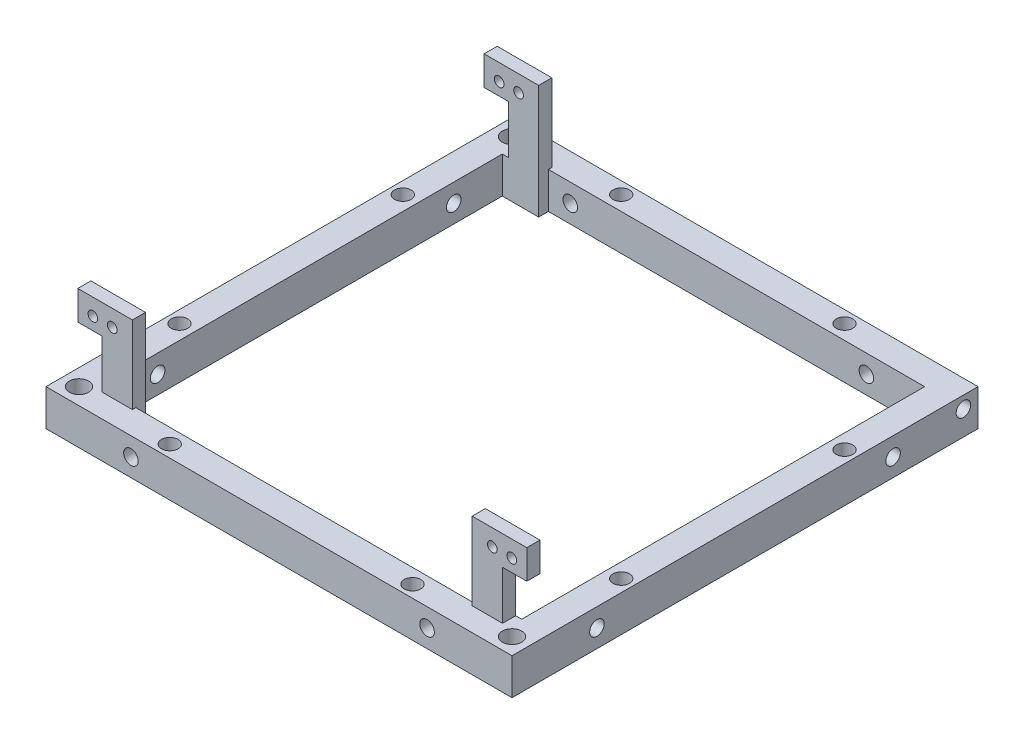
SolidWorks part; units mm, degrees
material "Aluminum"
ref_plane "Front Plane" through (0, 0, 0) normal (0, 0, 1) x (1, 0, 0)
ref_plane "Top Plane" through (0, 0, 0) normal (0, 1, 0) x (1, 0, 0)
ref_plane "Right Plane" through (0, 0, 0) normal (1, 0, 0) x (0, 0, -1)
sketch "Sketch1" plane through (0, 0, 0) normal (0, 1, 0) x (1, 0, 0)
  line L1 (48, -48) -> (-48, -48)
  line L2 (48, -48) -> (48, 48)
  line L3 (48, 48) -> (-48, 48)
  line L4 (-48, -48) -> (-48, 48)
  line L5 (48, -48) -> (-48, 48) construction
  line L6 (48, 48) -> (-48, -48) construction
  line L7 (40, -40) -> (-40, -40)
  line L8 (40, -40) -> (40, 40)
  line L9 (40, 40) -> (-40, 40)
  line L10 (-40, -40) -> (-40, 40)
  line L11 (40, -40) -> (-40, 40) construction
  line L12 (40, 40) -> (-40, -40) construction
  point P0 (0, 0)
  point P6 (0, 0)
  dimension "D1" = 96
  dimension "D2" = 96
  dimension "D3" = 8
extrude "Boss-Extrude1" add sketch "Sketch1" along normal blind 8
sketch "Sketch27" plane through (0, 8, 0) normal (0, 1, 0) x (1, 0, 0)
  line L0 (-40, 40) -> (-40, -40) construction
  line L1 (41, -41) -> (-41, -41)
  line L2 (41, -41) -> (41, 41)
  line L3 (41, 41) -> (-41, 41)
  line L4 (-41, -41) -> (-41, 41)
  line L5 (41, -41) -> (-41, 41) construction
  line L6 (41, 41) -> (-41, -41) construction
  line L7 (40, 40) -> (-40, 40) construction
  point P0 (0, 0)
  dimension "D1" = 1
  dimension "D2" = 1
extrude "Cut-Extrude2" cut sketch "Sketch27" against normal blind 10
hole_wizard "Ø3.0 (3) Diameter Hole1" positions "Sketch30" profile "Sketch29" hole size "Ø3.0" standard "ANSI Metric" end condition through all
sketch "Sketch30" plane through (0, 0, 48) normal (0, 0, 1) x (1, 0, 0)
  point P0 (-30.5, 2.7)
  point P4 (30.5, 2.7)
sketch "Sketch29" plane through (-30.5, 2.7, 48) normal (1, 0, 0) x (0, -1, 0)
  line L0 (0, 0) -> (0, 96)
  line L1 (0, 96) -> (1.5, 96)
  line L2 (1.5, 96) -> (1.5, 0)
  line L5 (1.5, 0) -> (0, 0)
  line L11 (0, -6.35) -> (0, 107.95) construction
  dimension "Thru Hole Dia." = 3
  dimension "Thru Hole Depth" = 96
hole_wizard "Ø3.4 (3.4) Diameter Hole1" positions "Sketch37" profile "Sketch36" hole size "Ø3.4" standard "ANSI Metric" end condition through all
sketch "Sketch37" plane through (0, 0, 0) normal (0, -1, 0) x (-1, 0, 0)
  point P0 (-23, 45.5)
  point P2 (23, 45.5)
  point P4 (45.5, 23)
  point P6 (45.5, -23)
  point P8 (25, -45.5)
  point P10 (-25, -45.5)
  point P12 (-45.5, -23)
  point P14 (-45.5, 23)
sketch "Sketch36" plane through (23, 0, -45.5) normal (1, 0, 0) x (0, 0, -1)
  line L0 (0, 0) -> (0, 8)
  line L1 (0, 8) -> (1.7, 8)
  line L2 (1.7, 8) -> (1.7, 0)
  line L5 (1.7, 0) -> (0, 0)
  line L11 (0, -6.35) -> (0, 107.95) construction
  dimension "Thru Hole Dia." = 3.4
  dimension "Thru Hole Depth" = 8
sketch "Sketch38" plane through (0, 8, 0) normal (0, 1, 0) x (1, 0, 0)
  line L0 (48, 48) -> (-48, 48) construction
  line L1 (42.5, -42.5) -> (-42.5, -42.5)
  line L2 (42.5, -42.5) -> (42.5, 42.5)
  line L3 (42.5, 42.5) -> (-42.5, 42.5)
  line L4 (-42.5, -42.5) -> (-42.5, 42.5)
  line L5 (42.5, -42.5) -> (-42.5, 42.5) construction
  line L6 (42.5, 42.5) -> (-42.5, -42.5) construction
  line L7 (-48, 48) -> (-48, -48) construction
  point P0 (0, 0)
  dimension "D1" = 5.5
  dimension "D2" = 5.5
extrude "Cut-Extrude4" cut sketch "Sketch38" against normal blind 10
hole_wizard "Ø3.0 (3) Diameter Hole7" positions "Sketch40" profile "Sketch41" hole size "Ø3.0" standard "ISO" end condition through all
sketch "Sketch40" plane through (-48, 0, 0) normal (-1, 0, 0) x (0, 0, 1)
  line L0 (0, 0) -> (0, 8) construction
  line L1 (-48, 0) -> (48, 0) construction
  line L2 (-48, 8) -> (48, 8) construction
  point P0 (-30.5, 2.7)
  point P2 (30.5, 2.7)
  dimension "D1" = 61
  dimension "D2" = 30.5
sketch "Sketch41" plane through (-48, 2.7, -30.5) normal (0, 1, 0) x (0, 0, 1)
  line L0 (0, 0) -> (0, 96)
  line L1 (0, 96) -> (1.5, 96)
  line L2 (1.5, 96) -> (1.5, 0)
  line L5 (1.5, 0) -> (0, 0)
  line L11 (0, -6.35) -> (0, 107.95) construction
  dimension "Thru Hole Dia." = 3
  dimension "Thru Hole Depth" = 96
sketch "Sketch44" plane through (0, 0, 0) normal (0, -1, 0) x (1, 0, 0)
  line L0 (42.5, -42.5) -> (-42.5, -42.5) construction
  line L1 (42.5, -42.5) -> (38.5, -42.5)
  line L2 (42.5, -42.5) -> (42.5, -38.5)
  line L3 (42.5, -38.5) -> (38.5, -38.5)
  line L4 (38.5, -42.5) -> (38.5, -38.5)
  line L5 (42.5, 42.5) -> (42.5, -42.5) construction
  line L6 (0, 0) -> (0, -67.1068) construction
  line L7 (0, 0) -> (66.4168, 0) construction
  line L8 (-38.5, -42.5) -> (-38.5, -38.5)
  line L9 (-42.5, -38.5) -> (-38.5, -38.5)
  line L10 (-42.5, -42.5) -> (-42.5, -38.5)
  line L11 (-42.5, -42.5) -> (-38.5, -42.5)
  line L12 (-42.5, 42.5) -> (-38.5, 42.5)
  line L13 (-42.5, 42.5) -> (-42.5, 38.5)
  line L14 (-42.5, 38.5) -> (-38.5, 38.5)
  line L15 (-38.5, 42.5) -> (-38.5, 38.5)
  line L16 (38.5, 42.5) -> (38.5, 38.5)
  line L17 (42.5, 38.5) -> (38.5, 38.5)
  line L18 (42.5, 42.5) -> (42.5, 38.5)
  line L19 (42.5, 42.5) -> (38.5, 42.5)
  dimension "D1" = 4
  dimension "D2" = 4
extrude "Boss-Extrude2" add sketch "Sketch44" against normal blind 8
sketch "Sketch45" plane through (0, 8, 0) normal (0, 1, 0) x (1, 0, 0)
  line L1 (-42.5, 38.5) -> (-38.5, 38.5)
  line L2 (-42.5, 38.5) -> (-42.5, 35)
  line L3 (-42.5, 35) -> (-38.5, 35)
  line L4 (-38.5, 38.5) -> (-38.5, 35)
  dimension "D1" = 4
  dimension "D2" = 3.5
extrude "Boss-Extrude3" add sketch "Sketch45" against normal blind 8
sketch "Sketch49" plane through (48, 0, 0) normal (1, 0, 0) x (0, 0, -1)
  line L0 (48, 8) -> (48, 0) construction
  line L1 (-48, 8) -> (48, 8)
  line L2 (-48, 8) -> (-48, 6.5)
  line L3 (-48, 6.5) -> (48, 6.5)
  line L4 (48, 8) -> (48, 6.5)
  dimension "D1" = 1.5
extrude "Cut-Extrude5" cut sketch "Sketch49" against normal blind 146
hole_wizard "Tap Drill for M4 Tap1" positions "Sketch51" profile "Sketch50" hole size "M4" standard "ISO" end condition through all
sketch "Sketch51" plane through (0, 6.5, 0) normal (0, 1, 0) x (1, 0, 0)
  line L1 (-48, -48) -> (48, -48) construction
  line L2 (48, -48) -> (48, 48) construction
  line L3 (-48, -48) -> (-48, 48) construction
  line L4 (-48, 48) -> (48, 48) construction
  point P0 (44.6, -44.6)
  point P4 (-44.6, -44.6)
  point P6 (-44.6, 44.6)
  dimension "D1" = 3.4
  dimension "D2" = 3.4
  dimension "D3" = 3.4
  dimension "D4" = 3.4
  dimension "D5" = 3.4
  dimension "D6" = 3.4
sketch "Sketch50" plane through (44.6, 6.5, 44.6) normal (1, 0, 0) x (0, 0, 1)
  line L0 (0, 0) -> (0, 6.5)
  line L1 (0, 6.5) -> (2, 6.5)
  line L2 (2, 6.5) -> (2, 0)
  line L5 (2, 0) -> (0, 0)
  line L11 (0, -6.35) -> (0, 107.95) construction
  dimension "Thru Hole Dia." = 4
  dimension "Thru Hole Depth" = 6.5
sketch "Sketch53" plane through (-38.5, 0, 0) normal (1, 0, 0) x (0, 0, -1)
  line L1 (-42.5, 6.5) -> (-38.5, 6.5)
  line L2 (-42.5, 6.5) -> (-42.5, 0)
  line L3 (-42.5, 0) -> (-38.5, 0)
  line L4 (-38.5, 6.5) -> (-38.5, 0)
extrude "Boss-Extrude5" add sketch "Sketch53" along normal blind 78
sketch "Sketch54" plane through (0, 6.5, 0) normal (0, 1, 0) x (1, 0, 0)
  line L0 (42.5, -38.5) -> (-42.5, -38.5) construction
  line L1 (-42.5, 35) -> (-42.5, -38.5) construction
  line L2 (-48, -48) -> (48, -48) construction
  line L3 (-41.25, -40.5) -> (-41.25, -43.2)
  line L6 (0, -38.5) -> (0, -84.4574) construction
  line L7 (-35, -40.5) -> (-35, -43.2)
  line L8 (-41.25, -43.2) -> (-35, -43.2)
  line L10 (-41.25, -40.5) -> (-35, -40.5)
  line L11 (0, 0) -> (25.8217, 0) construction
  dimension "D1" = 2.7
  dimension "D2" = 4.8
  dimension "D3" = 6.25
  dimension "D4" = 1.25
  dimension "D5" = 6.25
  dimension "D6" = 2.7
sketch "Sketch57" plane through (0, 0, -35) normal (0, 0, 1) x (1, 0, 0)
  line L1 (-42.5, 6.5) -> (-38.5, 6.5)
  line L2 (-42.5, 6.5) -> (-42.5, 0)
  line L3 (-42.5, 0) -> (-38.5, 0)
  line L4 (-38.5, 6.5) -> (-38.5, 0)
extrude "Cut-Extrude6" cut sketch "Sketch57" against normal blind 7.5
sketch "Sketch58" plane through (38.5, 0, 0) normal (-1, 0, 0) x (0, 0, 1)
  line L1 (-42.5, 6.5) -> (-38.5, 6.5)
  line L2 (-42.5, 6.5) -> (-42.5, 0)
  line L3 (-42.5, 0) -> (-38.5, 0)
  line L4 (-38.5, 6.5) -> (-38.5, 0)
extrude "Boss-Extrude7" add sketch "Sketch58" along normal blind 81
sketch "Sketch61" plane through (0, 6.5, 0) normal (0, 1, 0) x (1, 0, 0)
  line L0 (-48, 48) -> (48, 48) construction
  line L1 (-16, 42.5) -> (16, 42.5)
  line L2 (-16, 42.5) -> (-16, -42.5)
  line L3 (-16, -42.5) -> (16, -42.5)
  line L4 (16, 42.5) -> (16, -42.5)
  line L5 (-48, -48) -> (48, -48) construction
  dimension "D1" = 5.5
  dimension "D2" = 5.5
  dimension "D3" = 16
  dimension "D4" = 16
extrude "Cut-Extrude7" cut sketch "Sketch61" against normal blind 81
sketch "Sketch66" plane through (0, 6.5, 0) normal (0, 1, 0) x (1, 0, 0)
  line L0 (42.5, -38.5) -> (42.5, 38.5) construction
  line L1 (42.5, 40.099) -> (-42.5, 40.099)
  line L2 (42.5, 40.099) -> (42.5, -40.099)
  line L3 (42.5, -40.099) -> (-42.5, -40.099)
  line L4 (-42.5, 40.099) -> (-42.5, -40.099)
  line L5 (-42.5, 38.5) -> (-42.5, -38.5) construction
extrude "Cut-Extrude8" cut sketch "Sketch66" against normal blind 10
sketch "Sketch67" plane through (0, 0, 0) normal (0, -1, 0) x (1, 0, 0)
  line L0 (42.5, 40.099) -> (42.5, -40.099) construction
  line L1 (-42.5, 42.5) -> (42.5, 42.5)
  line L2 (-42.5, 42.5) -> (-42.5, -42.5)
  line L3 (-42.5, -42.5) -> (42.5, -42.5)
  line L4 (42.5, 42.5) -> (42.5, -42.5)
  line L5 (-16, 42.5) -> (16, 42.5) construction
  line L6 (-42.5, -40.099) -> (-42.5, 40.099) construction
  line L7 (16, -42.5) -> (-16, -42.5) construction
extrude "Cut-Extrude9" cut sketch "Sketch67" against normal blind 3.5
sketch "Sketch68" plane through (0, 6.5, 0) normal (0, 1, 0) x (1, 0, 0)
  line L1 (26, 42.5) -> (-26, 42.5)
  line L2 (26, 42.5) -> (26, -42.5)
  line L3 (26, -42.5) -> (-26, -42.5)
  line L4 (-26, 42.5) -> (-26, -42.5)
  line L5 (0, 0) -> (0, 30.6776) construction
  line L6 (16, 42.5) -> (-16, 42.5) construction
  dimension "D1" = 26
  dimension "D2" = 26
extrude "Cut-Extrude10" cut sketch "Sketch68" against normal blind 56
extrude "Boss-Extrude8" add sketch "Sketch54" along normal blind 16
mirror "Mirror1" about plane through (0, 0, 0) normal (1, 0, 0) of "Boss-Extrude8"
sketch "Sketch75" plane through (26, 0, 0) normal (-1, 0, 0) x (0, 0, 1)
  line L1 (40.099, 6.5) -> (42.5, 6.5)
  line L2 (40.099, 6.5) -> (40.099, 3.5)
  line L3 (40.099, 3.5) -> (42.5, 3.5)
  line L4 (42.5, 6.5) -> (42.5, 3.5)
extrude "Cut-Extrude12" cut sketch "Sketch75" against normal blind 10.22 and the other way blind 62.22
mirror "Mirror2" about plane through (0, 0, 0) normal (0, 0, 1) of "Boss-Extrude8"
mirror "Mirror3" about plane through (0, 0, 0) normal (0, 0, 1) of "Cut-Extrude12"
sketch "Sketch77" plane through (36.22, 0, 0) normal (-1, 0, 0) x (0, 0, 1)
  line L1 (-42.5, 6.5) -> (-40.099, 6.5)
  line L2 (-42.5, 6.5) -> (-42.5, 3.5)
  line L3 (-42.5, 3.5) -> (-40.099, 3.5)
  line L4 (-40.099, 6.5) -> (-40.099, 3.5)
extrude "Cut-Extrude13" cut sketch "Sketch77" against normal blind 6.28
sketch "Sketch78" plane through (0, 0, 0) normal (0, -1, 0) x (1, 0, 0)
  line L1 (-42.5, 42.5) -> (42.5, 42.5)
  line L2 (-42.5, 42.5) -> (-42.5, -42.5)
  line L3 (-42.5, -42.5) -> (42.5, -42.5)
  line L4 (42.5, 42.5) -> (42.5, -42.5)
extrude "Cut-Extrude14" cut sketch "Sketch78" against normal blind 6.5
sketch "Sketch79" plane through (0, 0, 0) normal (0, -1, 0) x (1, 0, 0)
  line L0 (40.5, -40.5) -> (40.5, 40.5)
  line L1 (42.5, -42.5) -> (-42.5, -42.5)
  line L2 (42.5, -42.5) -> (42.5, 42.5)
  line L3 (42.5, 42.5) -> (-42.5, 42.5)
  line L4 (-42.5, -42.5) -> (-42.5, 42.5)
  line L5 (40.5, 40.5) -> (-40.5, 40.5)
  line L6 (-40.5, -40.5) -> (-40.5, 40.5)
  line L7 (40.5, -40.5) -> (-40.5, -40.5)
  dimension "D1" = 2
extrude "Boss-Extrude12" add sketch "Sketch79" against normal blind 6.5
sketch "Sketch81" plane through (-41.25, 0, 0) normal (-1, 0, 0) x (0, 0, 1)
  line L0 (43.2, 22.5) -> (43.2, 6.5) construction
  line L1 (40.5, 22.5) -> (43.2, 22.5)
  line L2 (40.5, 22.5) -> (40.5, 16.5)
  line L3 (40.5, 16.5) -> (43.2, 16.5)
  line L4 (43.2, 22.5) -> (43.2, 16.5)
  dimension "D1" = 6
extrude "Boss-Extrude13" add sketch "Sketch81" along normal blind 5
mirror "Mirror4" about plane through (0, 0, 0) normal (0, 0, 1) of "Boss-Extrude13"
mirror "Mirror5" about plane through (0, 0, 0) normal (1, 0, 0) of "Boss-Extrude13"
hole_wizard "Tap Drill for M2 Tap1" positions "Sketch83" profile "Sketch82" hole size "M2" standard "ISO"
sketch "Sketch83" plane through (0, 0, 40.5) normal (0, 0, -1) x (-1, 0, 0)
  point P0 (39.1473, 19.1)
  point P3 (43.1473, 19.1)
  point P6 (-39.15, 19.1)
  point P9 (-43.15, 19.1)
sketch "Sketch82" plane through (-39.1473, 19.1, 40.5) normal (1, 0, 0) x (0, 1, 0)
  line L0 (0, 0) -> (0, 5.5)
  line L1 (0, 5.5) -> (1, 5.5)
  line L2 (1, 5.5) -> (1, 0)
  line L5 (1, 0) -> (0, 0)
  line L10 (0, 5.5) -> (-1, 5.5) construction
  line L11 (0, -6.35) -> (0, 107.95) construction
  dimension "Hole Dia." = 2
  dimension "Hole Depth" = 5.5
  dimension "Drill Angle" = 180
hole_wizard "Tap Drill for M2 Tap2" positions "Sketch85" profile "Sketch84" hole size "M2" standard "ISO"
sketch "Sketch85" plane through (0, 0, -40.5) normal (0, 0, 1) x (1, 0, 0)
  point P0 (-39.1473, 19.1)
  point P3 (-43.1473, 19.1)
sketch "Sketch84" plane through (-39.1473, 19.1, -40.5) normal (1, 0, 0) x (0, -1, 0)
  line L0 (0, 0) -> (0, 5.5)
  line L1 (0, 5.5) -> (1, 5.5)
  line L2 (1, 5.5) -> (1, 0)
  line L5 (1, 0) -> (0, 0)
  line L10 (0, 5.5) -> (-1, 5.5) construction
  line L11 (0, -6.35) -> (0, 107.95) construction
  dimension "Hole Dia." = 2
  dimension "Hole Depth" = 5.5
  dimension "Drill Angle" = 180
hole_wizard "Tap Drill for M3x0.5 Tap1" positions "Sketch87" profile "Sketch86" hole size "M3x0.5" standard "ANSI Metric"
sketch "Sketch87" plane through (48, 0, 0) normal (1, 0, 0) x (0, 0, -1)
  point P0 (45, 4)
sketch "Sketch86" plane through (48, 4, -45) normal (0, 1, 0) x (0, 0, -1)
  line L0 (0, 0) -> (0, 7.5)
  line L1 (0, 7.5) -> (1.5, 7.5)
  line L2 (1.5, 7.5) -> (1.5, 0)
  line L5 (1.5, 0) -> (0, 0)
  line L10 (0, 7.5) -> (-1.5, 7.5) construction
  line L11 (0, -6.35) -> (0, 107.95) construction
  dimension "Hole Dia." = 3
  dimension "Hole Depth" = 7.5
  dimension "Drill Angle" = 180
sketch "Sketch88" plane through (0, 6.5, 0) normal (0, 1, 0) x (1, 0, 0)
  line L0 (40.5, 40.5) -> (40.5, -40.5) construction
  line L1 (40.5, 35) -> (42.5, 35)
  line L2 (40.5, 35) -> (40.5, -35)
  line L3 (40.5, -35) -> (42.5, -35)
  line L4 (42.5, 35) -> (42.5, -35)
  line L5 (-35, 40.5) -> (40.5, 40.5) construction
  line L6 (35, -40.5) -> (-35, -40.5) construction
  line L7 (-40.5, -40.5) -> (-40.5, 40.5) construction
  line L8 (35, -40.5) -> (-35, -40.5)
  line L9 (35, -40.5) -> (35, -42.5)
  line L10 (35, -42.5) -> (-35, -42.5)
  line L11 (-35, -40.5) -> (-35, -42.5)
  line L13 (-40.5, -35) -> (-42.5, -35)
  line L14 (-40.5, -35) -> (-40.5, 35)
  line L15 (-40.5, 35) -> (-42.5, 35)
  line L16 (-42.5, -35) -> (-42.5, 35)
  line L17 (35, 40.5) -> (-35, 40.5)
  line L18 (35, 40.5) -> (35, 42.5)
  line L19 (35, 42.5) -> (-35, 42.5)
  line L20 (-35, 40.5) -> (-35, 42.5)
  dimension "D1" = 5.5
  dimension "D2" = 5.5
  dimension "D3" = 2
  dimension "D4" = 2
  dimension "D5" = 5.5
  dimension "D6" = 5.5
  dimension "D7" = 5.5
  dimension "D8" = 5.5
  dimension "D9" = 2
  dimension "D10" = 2
  dimension "D11" = 5.5
  dimension "D12" = 5.5
extrude "Cut-Extrude15" cut sketch "Sketch88" against normal blind 10
sketch "Sketch89" plane through (0, 6.5, 0) normal (0, 1, 0) x (1, 0, 0)
  line L0 (-35, 40.5) -> (-46.25, 40.5) construction
  line L1 (-42.5, 40.5) -> (42.5, 40.5)
  line L2 (-42.5, 40.5) -> (-42.5, -40.5)
  line L3 (-42.5, -40.5) -> (42.5, -40.5)
  line L4 (42.5, 40.5) -> (42.5, -40.5)
  line L5 (35, -40.5) -> (46.25, -40.5) construction
extrude "Cut-Extrude16" cut sketch "Sketch89" against normal blind 10
sketch "Sketch90" plane through (35, 0, 0) normal (-1, 0, 0) x (0, 0, 1)
  line L1 (-42.5, 0) -> (-40.5, 0)
  line L2 (-42.5, 0) -> (-42.5, 6.5)
  line L3 (-42.5, 6.5) -> (-40.5, 6.5)
  line L4 (-40.5, 0) -> (-40.5, 6.5)
extrude "Cut-Extrude17" cut sketch "Sketch90" against normal blind 7.5
sketch "Sketch91" plane through (0, 0, 0) normal (0, -1, 0) x (1, 0, 0)
  line L1 (-48, 48) -> (48, 48)
  line L2 (-48, 48) -> (-48, -48)
  line L3 (-48, -48) -> (48, -48)
  line L4 (48, 48) -> (48, -48)
  line L5 (42.5, -42.5) -> (-35, -42.5)
  line L6 (42.5, -42.5) -> (42.5, 40.5)
  line L7 (35, 42.5) -> (-35, 42.5)
  line L8 (-42.5, -40.5) -> (-42.5, 40.5)
  line L9 (-35, 40.5) -> (-42.5, 40.5)
  line L10 (-35, 40.5) -> (-35, 42.5)
  line L13 (35, 40.5) -> (42.5, 40.5)
  line L14 (35, 40.5) -> (35, 42.5)
  line L19 (-42.5, -40.5) -> (-35, -40.5)
  line L20 (-35, -42.5) -> (-35, -40.5)
  circle A0 centre (-25, 45.5) radius 1.7
  circle A1 centre (25, 45.5) radius 1.6454
  circle A2 centre (44.6, 44.6) radius 2
  circle A3 centre (45.5, 23) radius 1.7
  circle A4 centre (45.5, -23) radius 1.7
  circle A5 centre (23, -45.5) radius 1.7
  circle A6 centre (-23, -45.5) radius 1.7
  circle A7 centre (-45.5, -23) radius 1.7
  circle A8 centre (-44.6, -44.6) radius 2
  circle A9 centre (-45.5, 23) radius 1.7
  circle A10 centre (-44.6, 44.6) radius 2
extrude "Boss-Extrude14" add sketch "Sketch91" along normal blind 1
